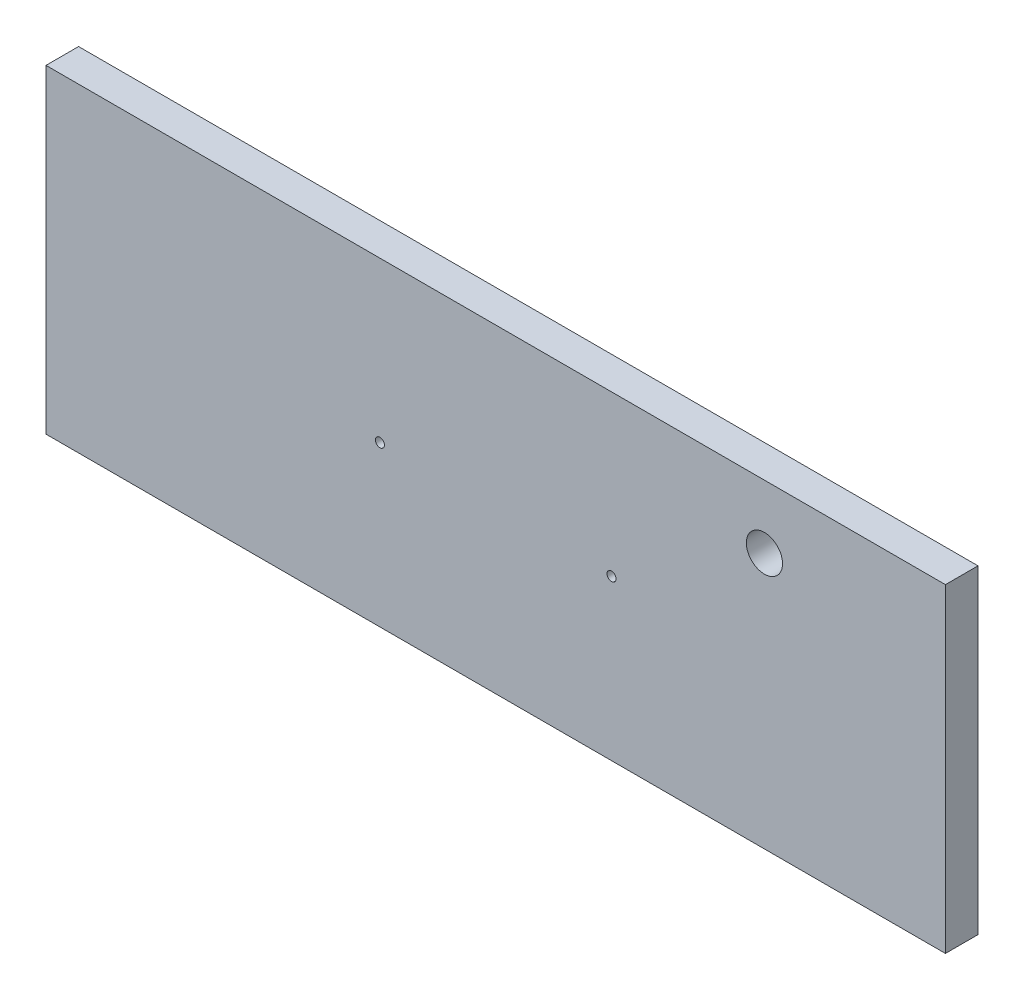
SolidWorks part; units mm, degrees
ref_plane "Front Plane" through (0, 0, 0) normal (0, 0, 1) x (1, 0, 0)
ref_plane "Top Plane" through (0, 0, 0) normal (0, 1, 0) x (1, 0, 0)
ref_plane "Right Plane" through (0, 0, 0) normal (1, 0, 0) x (0, 0, -1)
sketch "Sketch1" plane through (0, 0, 0) normal (0, 0, 1) x (1, 0, 0)
  line L0 (248.5, -35) -> (-248.5, -35) construction
  line L1 (-248.5, -211.5) -> (-248.5, -35) construction
  line L2 (248.5, -211.5) -> (-248.5, -211.5) construction
  line L3 (248.5, -211.5) -> (248.5, -35) construction
  line L4 (248.5, -35) -> (-248.5, -35)
  line L5 (-248.5, -211.5) -> (-248.5, -35)
  line L6 (248.5, -211.5) -> (-248.5, -211.5)
  line L7 (248.5, -211.5) -> (248.5, -35)
  dimension "D1" = 497
  dimension "D2" = 176.5
extrude "Boss-Extrude1" add sketch "Sketch1" along normal blind 18
extrude "Cut-Extrude3" cut sketch "Sketch4" against normal blind 18
sketch "Sketch4" plane through (0, 0, 18) normal (0, 0, 1) x (1, 0, 0)
  line L0 (0, -35) -> (0, -211.5) construction
  circle A0 centre (64, -123.25) radius 2.5
  circle A1 centre (-64, -123.25) radius 2.5
extrude "Cut-Extrude4" cut sketch "Sketch5" against normal blind 18
sketch "Sketch5" plane through (0, 0, 18) normal (0, 0, 1) x (1, 0, 0)
  circle A0 centre (148.5, -70) radius 10
extrude "Cut-Extrude5" cut sketch "Sketch6" against normal blind 12
sketch "Sketch6" plane through (0, 0, 0) normal (0, 0, -1) x (-1, 0, 0)
  line L0 (0, -35) -> (0, -211.5) construction
  circle A0 centre (224, -101) radius 5
  circle A1 centre (-224, -101) radius 5
  circle A2 centre (224, -165) radius 5
  circle A3 centre (-224, -165) radius 5
  point P22 (216.5, -205.5)
